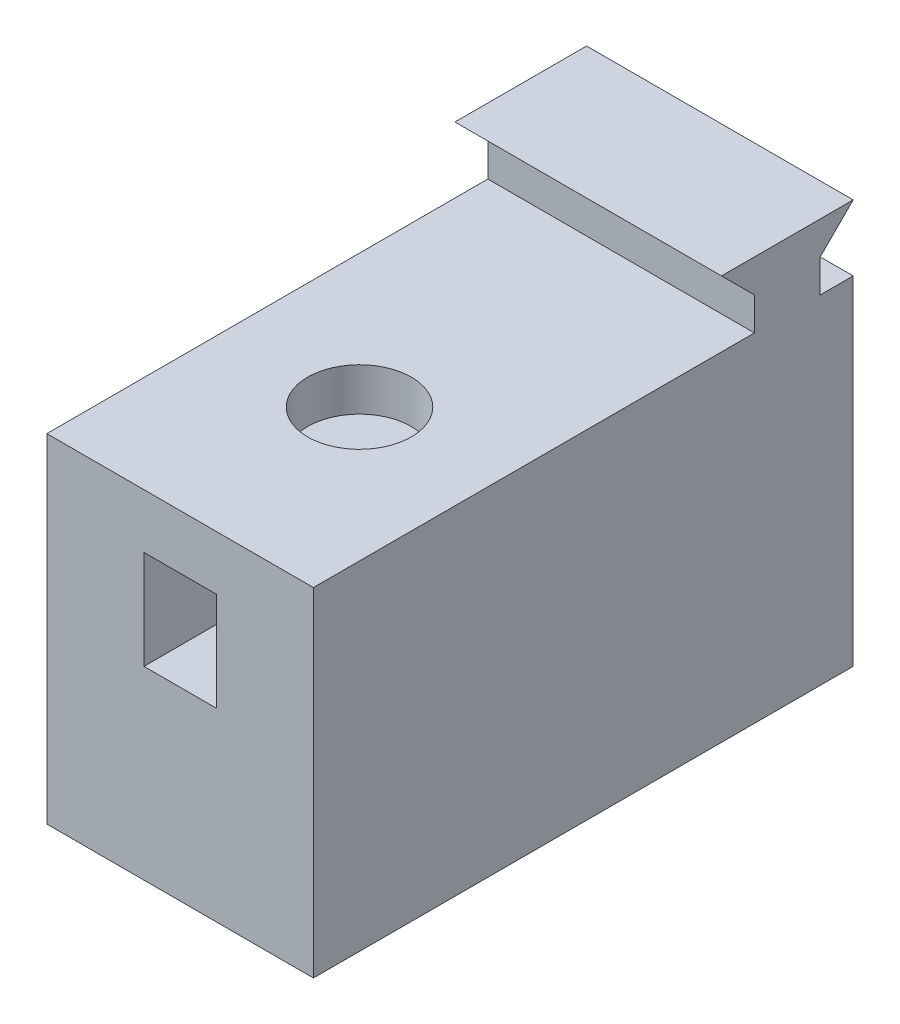
SolidWorks part; units mm, degrees
material "ABS"
ref_plane "Front Plane" through (0, 0, 0) normal (0, 0, 1) x (1, 0, 0)
ref_plane "Top Plane" through (0, 0, 0) normal (0, 1, 0) x (1, 0, 0)
ref_plane "Right Plane" through (0, 0, 0) normal (1, 0, 0) x (0, 0, -1)
sketch "Sketch1" plane through (0, 0, 0) normal (0, 1, 0) x (1, 0, 0)
  line L1 (-93.1, -10.9) -> (-76.9, -10.9)
  line L2 (-93.1, -10.9) -> (-93.1, 21.9)
  line L3 (-93.1, 21.9) -> (-76.9, 21.9)
  line L4 (-76.9, -10.9) -> (-76.9, 21.9)
extrude "Boss-Extrude1" add sketch "Sketch1" along normal mid plane 20.55 from offset 56.075
sketch "Sketch2" plane through (0, 0, 0) normal (1, 0, 0) x (0, 0, -1)
  line L0 (19.9, -46.3) -> (15.9, -46.3)
  line L1 (15.9, -46.3) -> (15.9, -43.8)
  line L2 (15.9, -43.8) -> (13.9, -41.8)
  line L3 (13.9, -41.8) -> (21.9, -41.8)
  line L4 (21.9, -41.8) -> (19.9, -43.8)
  line L5 (19.9, -43.8) -> (19.9, -46.3)
extrude "Boss-Extrude2" add sketch "Sketch2" along normal mid plane 16.2 from offset 85
sketch "Sketch3" plane through (0, 0, 0) normal (0, 1, 0) x (1, 0, 0)
  line L1 (-91.5, -6.1) -> (-78.5, -6.1)
  line L2 (-91.5, -6.1) -> (-91.5, 17.1)
  line L3 (-91.5, 17.1) -> (-78.5, 17.1)
  line L4 (-78.5, -6.1) -> (-78.5, 17.1)
extrude "Cut-Extrude1" cut sketch "Sketch3" against normal mid plane 17.25 from offset 57.725
sketch "Sketch4" plane through (0, 0, 0) normal (0, 1, 0) x (1, 0, 0)
  circle A0 centre (-85, 19.25) radius 1
extrude "Cut-Extrude2" cut sketch "Sketch4" against normal mid plane 6 from offset 63.35
sketch "Sketch5" plane through (0, 0, 0) normal (0, 1, 0) x (1, 0, 0)
  circle A0 centre (-85, -8.25) radius 1
extrude "Cut-Extrude3" cut sketch "Sketch5" against normal mid plane 6 from offset 63.35
sketch "Sketch6" plane through (0, 0, 0) normal (0, 1, 0) x (1, 0, 0)
  circle A0 centre (-85, 0) radius 3.15
extrude "Cut-Extrude4" cut sketch "Sketch6" against normal mid plane 2.6 from offset 47.1
sketch "Sketch7" plane through (0, 0, 0) normal (0, 0, 1) x (1, 0, 0)
  line L1 (-87.2, -55.1) -> (-82.8, -55.1)
  line L2 (-87.2, -55.1) -> (-87.2, -49.1)
  line L3 (-87.2, -49.1) -> (-82.8, -49.1)
  line L4 (-82.8, -55.1) -> (-82.8, -49.1)
extrude "Cut-Extrude5" cut sketch "Sketch7" against normal mid plane 4.8 from offset 8.5
